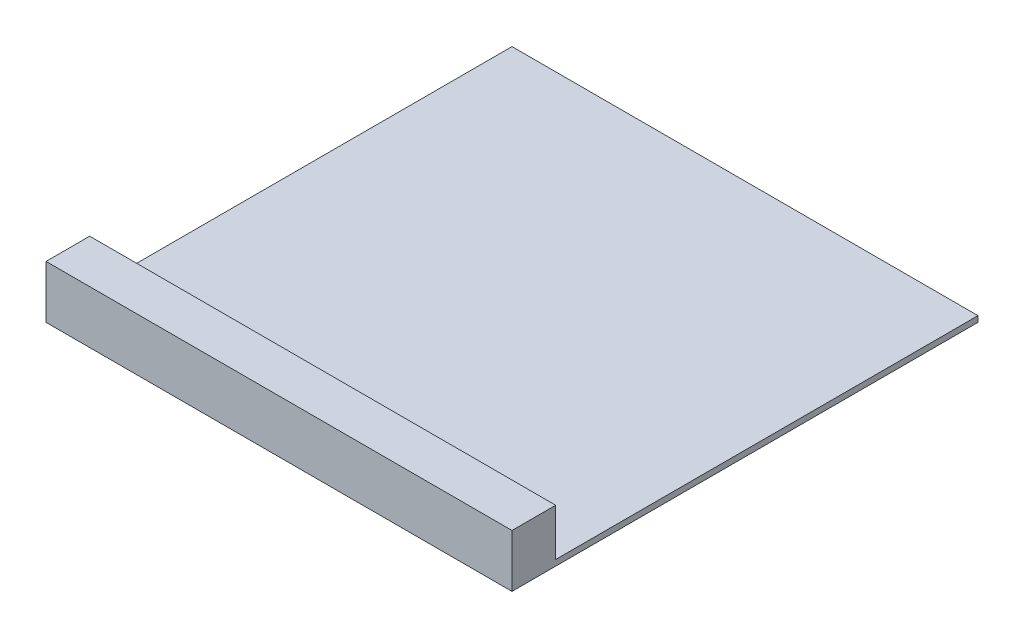
SolidWorks part; units mm, degrees
ref_plane "Front Plane" through (0, 0, 0) normal (0, 0, 1) x (1, 0, 0)
ref_plane "Top Plane" through (0, 0, 0) normal (0, 1, 0) x (1, 0, 0)
ref_plane "Right Plane" through (0, 0, 0) normal (1, 0, 0) x (0, 0, -1)
sketch "Sketch1" plane through (0, 0, 0) normal (0, 1, 0) x (1, 0, 0)
  line L1 (64, 64) -> (-64, 64)
  line L2 (64, 64) -> (64, -64)
  line L3 (64, -64) -> (-64, -64)
  line L4 (-64, 64) -> (-64, -64)
  line L5 (64, 64) -> (-64, -64) construction
  line L6 (64, -64) -> (-64, 64) construction
  point P0 (0, 0)
  dimension "D1" = 128
extrude "Boss-Extrude1" add sketch "Sketch1" along normal blind 14.5
sketch "Sketch2" plane through (0, 14.5, 0) normal (0, 1, 0) x (1, 0, 0)
  line L0 (64, -64) -> (64, 64) construction
  line L1 (-64, 64) -> (64, 64)
  line L2 (-64, 64) -> (-64, -52)
  line L3 (-64, -52) -> (64, -52)
  line L4 (64, 64) -> (64, -52)
  line L5 (-64, -64) -> (64, -64) construction
  dimension "D1" = 12
extrude "Cut-Extrude1" cut sketch "Sketch2" against normal offset from surface (12.9 mm away) 1.6 up to face at (0, 0, 0)
